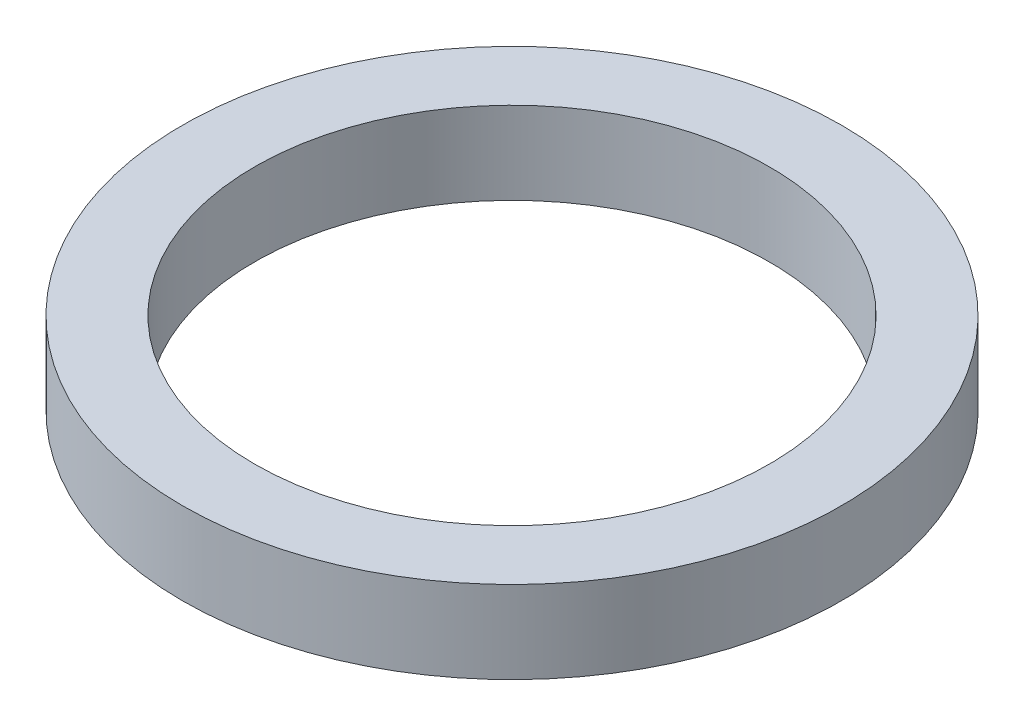
SolidWorks part; units mm, degrees
ref_plane "Front Plane" through (0, 0, 0) normal (0, 0, 1) x (1, 0, 0)
ref_plane "Top Plane" through (0, 0, 0) normal (0, 1, 0) x (1, 0, 0)
ref_plane "Right Plane" through (0, 0, 0) normal (1, 0, 0) x (0, 0, -1)
sketch "Sketch1" plane through (0, 14, 0) normal (0, 1, 0) x (1, 0, 0)
  line L0 (0, 0) -> (-0.5, 0)
  circle A0 centre (-0.5, 0) radius 16
  circle A1 centre (-0.5, 0) radius 12.5
  dimension "D1" = 32
  dimension "D2" = 25
extrude "Boss-Extrude1" add sketch "Sketch1" against normal blind 4 contours A0 | A1
